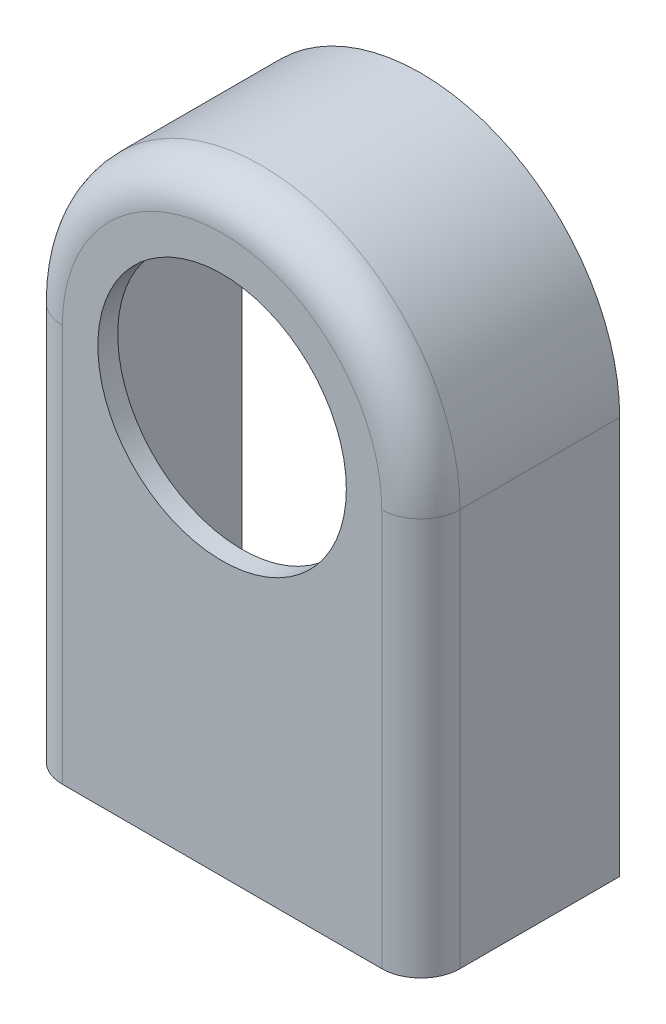
SolidWorks part; units mm, degrees
ref_plane "Front Plane" through (0, 0, 0) normal (0, 0, 1) x (1, 0, 0)
ref_plane "Top Plane" through (0, 0, 0) normal (0, 1, 0) x (1, 0, 0)
ref_plane "Right Plane" through (0, 0, 0) normal (1, 0, 0) x (0, 0, -1)
sketch "Sketch2" plane through (0, 0, 0) normal (0, 0, 1) x (1, 0, 0)
  line L1 (-50.8, 0) -> (-50.8, -101.6)
  line L2 (50.8, 0) -> (50.8, -101.6)
  line L3 (-50.8, -101.6) -> (50.8, -101.6)
  arc A0 (50.8, 0) -> (-50.8, 0) centre (0, 0) ccw
  point P1 (0, 0)
  dimension "D1" = 101.6
  dimension "D2" = 50.8
  dimension "D3" = 101.6
extrude "Boss-Extrude1" add sketch "Sketch2" along normal blind 50.8
fillet "Fillet1" radius 10 3 edges at (50.8, -50.8, 50.8) (-50.8, -50.8, 50.8) (0, 50.8, 50.8)
shell "Shell1" thickness 5.08
sketch "Sketch3" plane through (0, 0, 50.8) normal (0, 0, 1) x (1, 0, 0)
  circle A0 centre (0, 0) radius 31.75
extrude "Cut-Extrude2" cut sketch "Sketch3" against normal through all
